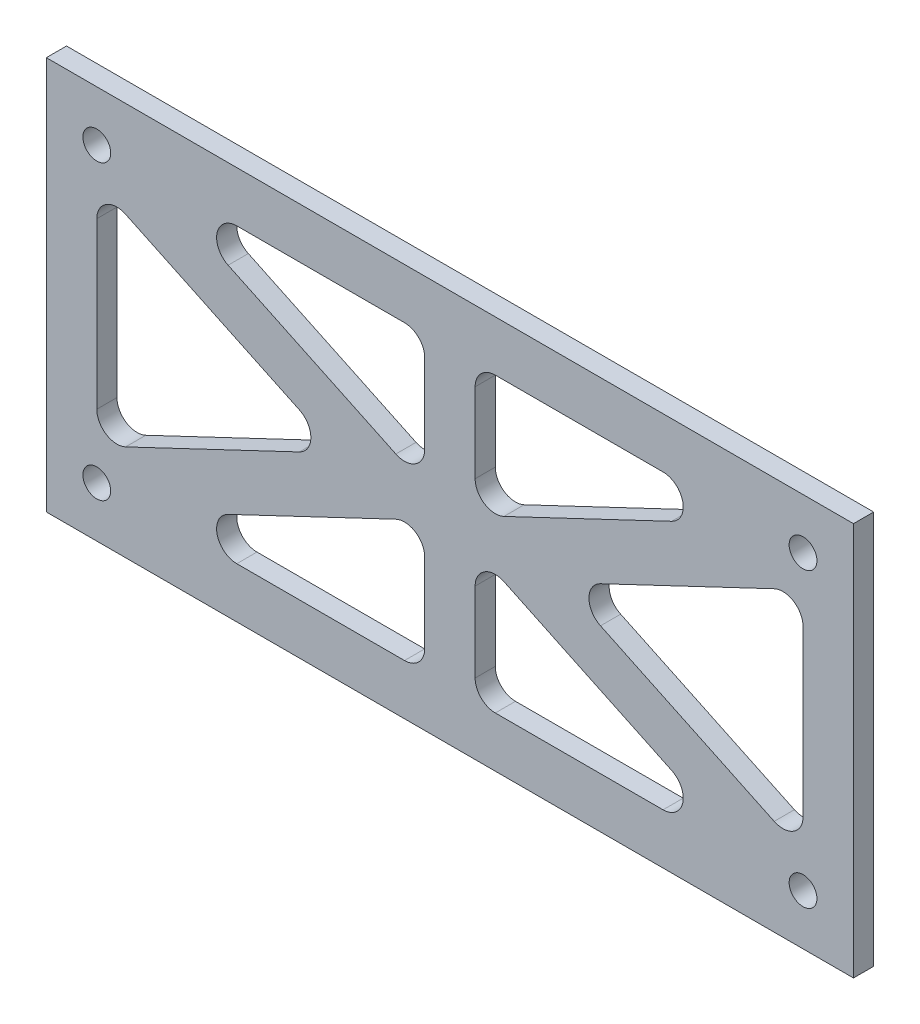
SolidWorks part; units mm, degrees
material "3.3549 (EN-AW 5182)"
ref_plane "Front Plane" through (0, 0, 0) normal (0, 0, 1) x (1, 0, 0)
ref_plane "Top Plane" through (0, 0, 0) normal (0, 1, 0) x (1, 0, 0)
ref_plane "Right Plane" through (0, 0, 0) normal (1, 0, 0) x (0, 0, -1)
sketch "Sketch1" plane through (0, 0, 0) normal (0, 0, 1) x (1, 0, 0)
  line L0 (50.8, 82.1269) -> (50.8, -21.7382) construction
  line L1 (2.54, 0) -> (99.06, 0)
  line L2 (0, 2.54) -> (0, 46.99)
  line L3 (2.54, 49.53) -> (99.06, 49.53)
  line L4 (101.6, 2.54) -> (101.6, 46.99)
  line L5 (143.6061, 24.765) -> (-42.0061, 24.765) construction
  line L15 (22.8822, 38.3455) -> (43.9956, 28.3209)
  line L16 (47.625, 30.6154) -> (47.625, 40.64)
  line L17 (45.085, 43.18) -> (23.9716, 43.18)
  line L21 (47.625, 18.9146) -> (47.625, 8.89)
  line L22 (22.8822, 11.1845) -> (43.9956, 21.2091)
  line L23 (45.085, 6.35) -> (23.9716, 6.35)
  line L24 (78.7178, 11.1845) -> (57.6044, 21.2091)
  line L25 (56.515, 6.35) -> (77.6284, 6.35)
  line L26 (53.975, 18.9146) -> (53.975, 8.89)
  line L33 (53.975, 30.6154) -> (53.975, 40.64)
  line L34 (78.7178, 38.3455) -> (57.6044, 28.3209)
  line L35 (56.515, 43.18) -> (77.6284, 43.18)
  line L36 (9.9794, 37.4423) -> (31.8473, 27.0595)
  line L37 (6.35, 35.1478) -> (6.35, 14.3822)
  line L39 (9.9794, 12.0877) -> (31.8473, 22.4705)
  line L40 (91.6206, 12.0877) -> (69.7527, 22.4705)
  line L41 (95.25, 35.1478) -> (95.25, 14.3822)
  line L42 (91.6206, 37.4423) -> (69.7527, 27.0595)
  line L43 (2.54, 49.53) -> (0, 49.53)
  line L44 (0, 49.53) -> (0, 46.99)
  line L45 (0, 2.54) -> (0, 0)
  line L46 (0, 0) -> (2.54, 0)
  line L47 (99.06, 0) -> (101.6, 0)
  line L48 (101.6, 0) -> (101.6, 2.54)
  line L49 (99.06, 49.53) -> (101.6, 49.53)
  line L50 (101.6, 49.53) -> (101.6, 46.99)
  circle A4 centre (6.35, 43.18) radius 1.7501
  circle A5 centre (6.35, 6.35) radius 1.7501
  circle A6 centre (95.25, 6.35) radius 1.7501
  circle A7 centre (95.25, 43.18) radius 1.7501
  arc A8 (53.975, 30.6154) -> (57.6044, 28.3209) centre (56.515, 30.6154) ccw
  arc A9 (53.975, 40.64) -> (56.515, 43.18) centre (56.515, 40.64) cw
  arc A10 (78.7178, 38.3455) -> (77.6284, 43.18) centre (77.6284, 40.64) ccw
  arc A17 (78.7178, 11.1845) -> (77.6284, 6.35) centre (77.6284, 8.89) cw
  arc A18 (56.515, 6.35) -> (53.975, 8.89) centre (56.515, 8.89) cw
  arc A19 (57.6044, 21.2091) -> (53.975, 18.9146) centre (56.515, 18.9146) ccw
  arc A20 (22.8822, 11.1845) -> (23.9716, 6.35) centre (23.9716, 8.89) ccw
  arc A21 (47.625, 8.89) -> (45.085, 6.35) centre (45.085, 8.89) cw
  arc A22 (47.625, 18.9146) -> (43.9956, 21.2091) centre (45.085, 18.9146) ccw
  arc A26 (43.9956, 28.3209) -> (47.625, 30.6154) centre (45.085, 30.6154) ccw
  arc A27 (47.625, 40.64) -> (45.085, 43.18) centre (45.085, 40.64) ccw
  arc A28 (22.8822, 38.3455) -> (23.9716, 43.18) centre (23.9716, 40.64) cw
  arc A29 (9.9794, 12.0877) -> (6.35, 14.3822) centre (8.89, 14.3822) cw
  arc A30 (31.8473, 22.4705) -> (31.8473, 27.0595) centre (30.7578, 24.765) ccw
  arc A31 (6.35, 35.1478) -> (9.9794, 37.4423) centre (8.89, 35.1478) cw
  arc A32 (91.6206, 12.0877) -> (95.25, 14.3822) centre (92.71, 14.3822) ccw
  arc A33 (69.7527, 22.4705) -> (69.7527, 27.0595) centre (70.8422, 24.765) cw
  arc A34 (95.25, 35.1478) -> (91.6206, 37.4423) centre (92.71, 35.1478) ccw
  point P2 (6.35, 43.18)
  point P7 (0, 0)
  point P10 (101.6, 0)
  point P13 (101.6, 49.53)
  point P16 (0, 49.53)
  point P24 (50.8, 24.765)
  point P37 (6.35, 10.3644)
  point P47 (36.6798, 24.765)
  point P50 (6.35, 39.1656)
  point P56 (53.975, 26.5977)
  point P59 (53.975, 43.18)
  point P62 (88.9, 43.18)
  point P65 (95.25, 26.9197)
  point P68 (95.25, 36.83)
  point P71 (50.6603, 26.9197)
  point P74 (50.6603, 22.6103)
  point P77 (95.25, 22.6103)
  point P80 (95.25, 12.7)
  point P83 (88.9, 6.35)
  point P86 (53.975, 6.35)
  point P89 (53.975, 22.9323)
  point P92 (12.7, 6.35)
  point P95 (47.625, 6.35)
  point P98 (47.625, 22.9323)
  point P101 (6.35, 12.7)
  point P104 (6.35, 22.6103)
  point P107 (50.9397, 22.6103)
  point P110 (47.625, 26.5977)
  point P113 (47.625, 43.18)
  point P116 (12.7, 43.18)
  point P119 (50.9397, 26.9197)
  point P122 (6.35, 26.9197)
  point P125 (6.35, 36.83)
  dimension "D4" = 3.5001
  dimension "D13" = 2.54
  dimension "D15" = 2.54
  dimension "D1" = 49.53
  dimension "D2" = 101.6
  dimension "D5" = 6.35
  dimension "D6" = 6.35
  dimension "D7" = 50.8
  dimension "D8" = 24.765
  dimension "D9" = 6.35
  dimension "D10" = 6.35
  dimension "D11" = 6.35
  dimension "D12" = 3.175
  dimension "D14" = 6.35
extrude "Boss-Extrude1" add sketch "Sketch1" along normal blind 2.54
